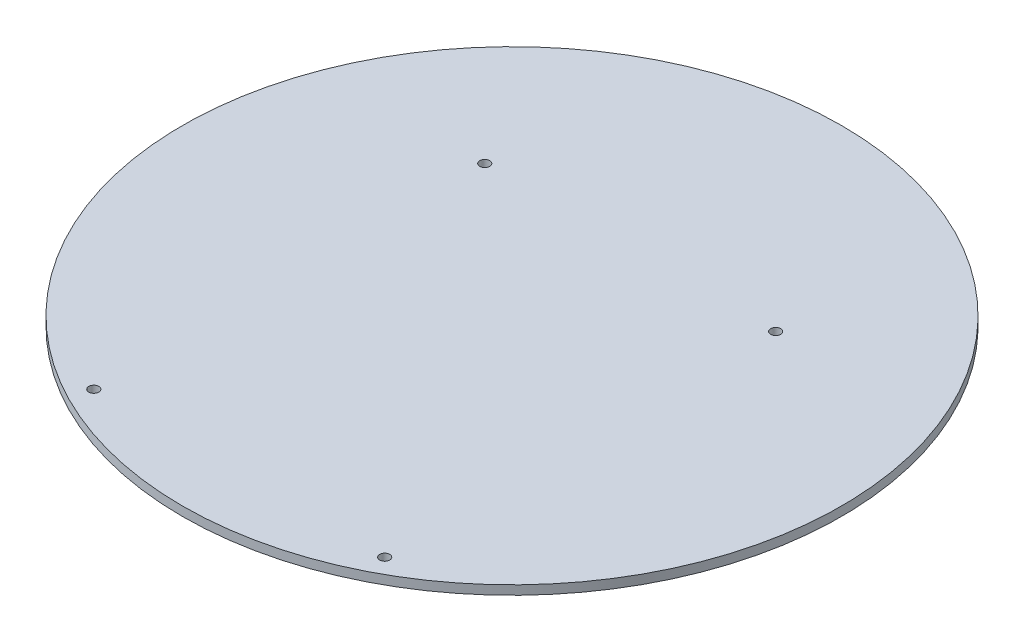
SolidWorks part; units mm, degrees
ref_plane "前视基准面" through (0, 0, 0) normal (0, 0, 1) x (1, 0, 0)
ref_plane "上视基准面" through (0, 0, 0) normal (0, 1, 0) x (1, 0, 0)
ref_plane "右视基准面" through (0, 0, 0) normal (1, 0, 0) x (0, 0, -1)
sketch "草图2" plane through (0, 0, 0) normal (0, 1, 0) x (1, 0, 0)
  circle A0 centre (0, 0) radius 72.5
  dimension "D1" = 145
extrude "凸台-拉伸1" add sketch "草图2" along normal blind 2
sketch "草图3" plane through (0, 0, 0) normal (0, -1, 0) x (1, 0, 0)
  line L0 (0, 0) -> (0, 17) construction
  line L1 (32, -26) -> (-32, -26) construction
  line L2 (32, -26) -> (32, 60) construction
  line L3 (32, 60) -> (-32, 60) construction
  line L4 (-32, -26) -> (-32, 60) construction
  line L5 (32, -26) -> (-32, 60) construction
  line L6 (32, 60) -> (-32, -26) construction
  circle A0 centre (32, 60) radius 1.1
  circle A1 centre (-32, 60) radius 1.1
  circle A2 centre (-32, -26) radius 1.1
  circle A4 centre (32, -26) radius 1.1
  point P0 (0, 17)
  dimension "D3" = 2.2
  dimension "D4" = 2.2
  dimension "D5" = 2.2
  dimension "D6" = 2.2
  dimension "D1" = 64
  dimension "D2" = 86
  dimension "D7" = 17
extrude "切除-拉伸1" cut sketch "草图3" against normal through all both and the other way through all
